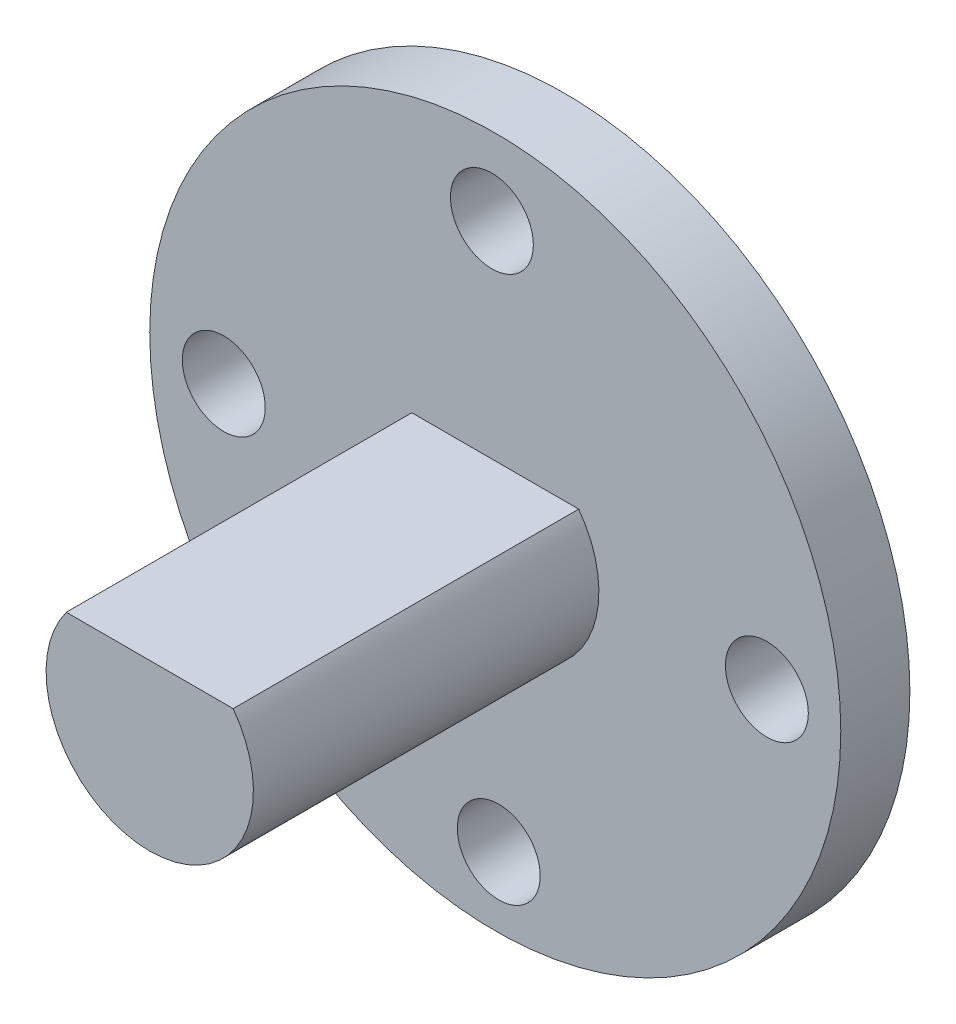
SolidWorks part; units mm, degrees
ref_plane "Plan de face" through (0, 0, 0) normal (0, 0, 1) x (1, 0, 0)
ref_plane "Plan de dessus" through (0, 0, 0) normal (0, 1, 0) x (1, 0, 0)
ref_plane "Plan de droite" through (0, 0, 0) normal (1, 0, 0) x (0, 0, -1)
sketch "Esquisse1" plane through (0, 0, 0) normal (0, 0, 1) x (1, 0, 0)
  circle A0 centre (0, 0) radius 10
  dimension "D1" = 20
extrude "Boss.-Extru.1" add sketch "Esquisse1" along normal blind 2
hole_wizard "Dégagement M21" positions "Esquisse3D1" profile "Esquisse3" hole size "M2" standard "Ansi Metric" end condition through all
sketch3d "Esquisse3D1"
  point P0 (-0.098, 7.7453, 2)
  dimension "D1" = 8
sketch "Esquisse3" plane through (-0.098, 7.7453, 2) normal (1, 0, 0) x (0, -1, 0)
  line L0 (0, 0) -> (0, 2)
  line L1 (0, 2) -> (1.2, 2)
  line L2 (1.2, 2) -> (1.2, 0)
  line L5 (1.2, 0) -> (0, 0)
  line L11 (0, -6.35) -> (0, 107.95) construction
  dimension "Diamètre du perçage jusqu'au prochain" = 2.4
  dimension "Profondeur du perçage jusqu'au prochain" = 2
pattern_circular "Répétition circulaire1" count 4 every 90 about axis through (0.0014, -0.1132, 0) along (0, 0, 1) of "Dégagement M21"
sketch "Esquisse4" plane through (0, 0, 2) normal (0, 0, 1) x (1, 0, 0)
  circle A0 centre (0, 0) radius 3
  dimension "D1" = 6
extrude "Boss.-Extru.2" add sketch "Esquisse4" along normal blind 10
sketch "Esquisse5" plane through (0, 0, 12) normal (0, 0, 1) x (1, 0, 0)
  line L1 (-3, 3) -> (3, 3)
  line L2 (-3, 3) -> (-3, 1.78)
  line L3 (-3, 1.78) -> (3, 1.78)
  line L4 (3, 3) -> (3, 1.78)
  circle A0 centre (0, 0) radius 3 construction
  dimension "D1" = 1.22
extrude "Enlèv. mat.-Extru.1" cut sketch "Esquisse5" against normal up to surface (10 mm away) up to face at (3, 0, 2)
